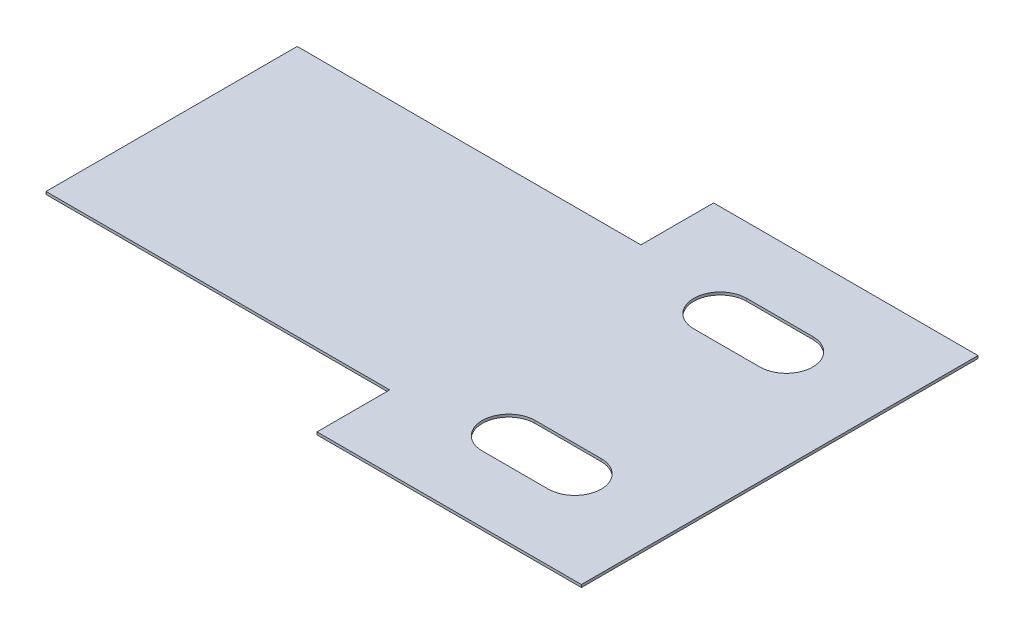
SolidWorks part; units mm, degrees
ref_plane "Front Plane" through (0, 0, 0) normal (0, 0, 1) x (1, 0, 0)
ref_plane "Top Plane" through (0, 0, 0) normal (0, 1, 0) x (1, 0, 0)
ref_plane "Right Plane" through (0, 0, 0) normal (1, 0, 0) x (0, 0, -1)
sketch "Sketch1" plane through (0, 0, 0) normal (0, 1, 0) x (1, 0, 0)
  line L20 (12.4712, 3.9627) -> (9.9712, 3.9627)
  line L21 (9.9712, 1.9627) -> (12.4712, 1.9627)
  line L22 (12.4712, -4.0373) -> (9.9712, -4.0373)
  line L23 (9.9712, -6.0373) -> (12.4712, -6.0373)
  line L24 (-6.7788, -5.7873) -> (6.2212, -5.7873)
  line L25 (6.2212, -5.7873) -> (6.2212, -8.5373)
  line L26 (6.2212, -8.5373) -> (16.2212, -8.5373)
  line L27 (16.2212, -8.5373) -> (16.2212, 6.4627)
  line L28 (16.2212, 6.4627) -> (6.2212, 6.4627)
  line L29 (6.2212, 6.4627) -> (6.2212, 3.7127)
  line L30 (6.2212, 3.7127) -> (-6.7788, 3.7127)
  line L31 (-6.7788, 3.7127) -> (-6.7788, -5.7873)
  arc A4 (9.9712, 3.9627) -> (9.9712, 1.9627) centre (9.9712, 2.9627) ccw
  arc A5 (12.4712, 1.9627) -> (12.4712, 3.9627) centre (12.4712, 2.9627) ccw
  arc A6 (9.9712, -4.0373) -> (9.9712, -6.0373) centre (9.9712, -5.0373) ccw
  arc A7 (12.4712, -6.0373) -> (12.4712, -4.0373) centre (12.4712, -5.0373) ccw
extrude "Boss-Extrude1" add sketch "Sketch1" along normal mid plane 0.1
